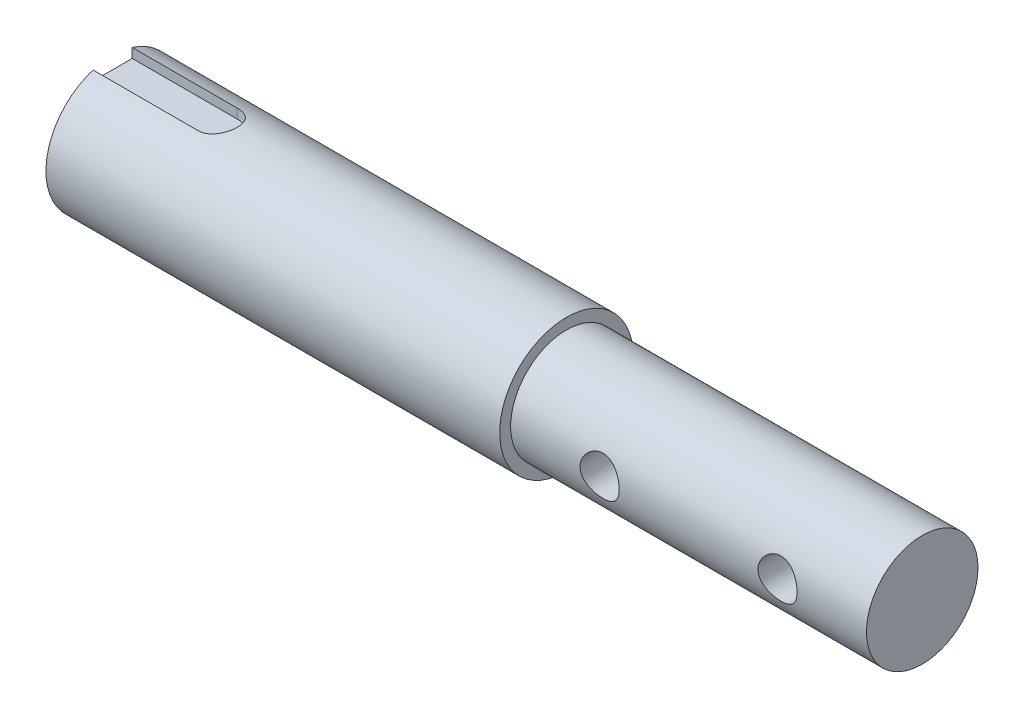
SolidWorks part; units mm, degrees
material "ASTM A36 Steel"
ref_plane "Front Plane" through (0, 0, 0) normal (0, 0, 1) x (1, 0, 0)
ref_plane "Top Plane" through (0, 0, 0) normal (0, 1, 0) x (1, 0, 0)
ref_plane "Right Plane" through (0, 0, 0) normal (1, 0, 0) x (0, 0, -1)
sketch "Sketch1" plane through (0, 0, 0) normal (1, 0, 0) x (0, 0, -1)
  circle A0 centre (0, 0) radius 37.5
  dimension "D1" = 75
extrude "Boss-Extrude1" add sketch "Sketch1" along normal blind 255
sketch "Sketch2" plane through (255, 0, 0) normal (1, 0, 0) x (0, 0, -1)
  circle A0 centre (0, 0) radius 31.34
  dimension "D1" = 62.68
extrude "Boss-Extrude2" add sketch "Sketch2" along normal blind 200
ref_plane "Plane1" through (0, 37.5, 0) normal (0, 1, 0) x (1, 0, 0)
sketch "Sketch3" plane through (0, 37.5, 0) normal (0, 1, 0) x (1, 0, 0)
  line L0 (0, 37.5) -> (0, -37.5) construction
  line L1 (59, -11) -> (0, -11)
  line L2 (0, -11) -> (0, 11)
  line L3 (0, 11) -> (59, 11)
  arc A0 (59, -11) -> (59, 11) centre (59, 0) ccw
  dimension "D1" = 22
  dimension "D2" = 59
extrude "Cut-Extrude1" cut sketch "Sketch3" against normal blind 7
sketch "Sketch4" plane through (0, 0, 0) normal (0, 0, 1) x (1, 0, 0)
  line L0 (255, -37.5) -> (255, 37.5) construction
  circle A0 centre (405, 0) radius 11
  circle A1 centre (305, 0) radius 11
  dimension "D1" = 22
  dimension "D2" = 50
  dimension "D3" = 22
  dimension "D4" = 100
extrude "Cut-Extrude2" cut sketch "Sketch4" against normal through all both and the other way through all
